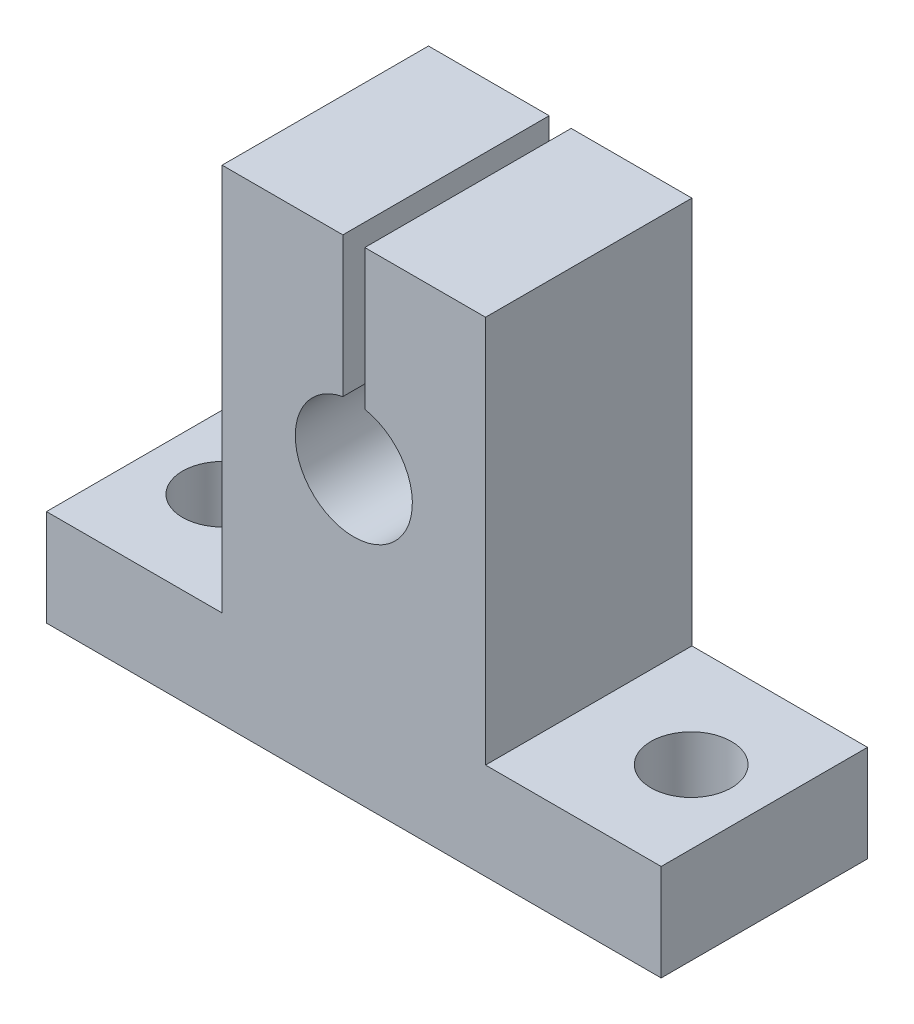
SolidWorks part; units mm, degrees
ref_plane "Front Plane" through (0, 0, 0) normal (0, 0, 1) x (1, 0, 0)
ref_plane "Top Plane" through (0, 0, 0) normal (0, 1, 0) x (1, 0, 0)
ref_plane "Right Plane" through (0, 0, 0) normal (1, 0, 0) x (0, 0, -1)
sketch "Sketch1" plane through (0, 0, 0) normal (0, 0, 1) x (1, 0, 0)
  line L0 (0, 0) -> (42, 0)
  line L1 (42, 0) -> (42, 6.6)
  line L2 (42, 6.6) -> (30, 6.6)
  line L3 (30, 6.6) -> (30, 33.1)
  line L4 (30, 33.1) -> (12, 33.1)
  line L5 (12, 33.1) -> (12, 6.6)
  line L6 (12, 6.6) -> (0, 6.6)
  line L7 (0, 6.6) -> (0, 0)
  point P3 (0, 6.7328)
  point P10 (0, 6.4551)
  dimension "D1" = 6.6
  dimension "D2" = 18
  dimension "D3" = 26.5
  dimension "D4" = 12
  dimension "D5" = 12
extrude "Boss-Extrude1" add sketch "Sketch1" against normal blind 14.1
sketch "Sketch2" plane through (0, 0, 0) normal (0, 0, 1) x (1, 0, 0)
  line L0 (30, 6.6) -> (30, 33.1) construction
  line L1 (30, 33.1) -> (12, 33.1) construction
  line L2 (20.25, 33.1) -> (21.75, 33.1)
  line L3 (21.75, 33.1) -> (21.75, 23.5291)
  line L5 (20.25, 33.1) -> (20.25, 23.5291)
  arc A0 (20.25, 23.5291) -> (21.75, 23.5291) centre (21, 19.6) ccw
  point P3 (21, 33.1)
  dimension "D3" = 13.5
  dimension "D4" = 4
  dimension "D1" = 1.5
  dimension "D2" = 9
  dimension "D5" = 9
extrude "Cut-Extrude1" cut sketch "Sketch2" against normal blind 14.1
sketch "Sketch3" plane through (0, 0, 0) normal (0, -1, 0) x (1, 0, 0)
  line L1 (0, 0) -> (42, 0) construction
  circle A0 centre (5, -7.05) radius 2.75
  circle A1 centre (37, -7.05) radius 2.75
  dimension "D1" = 5.5
  dimension "D4" = 5
  dimension "D2" = 7.05
  dimension "D3" = 32
extrude "Cut-Extrude2" cut sketch "Sketch3" against normal through all
